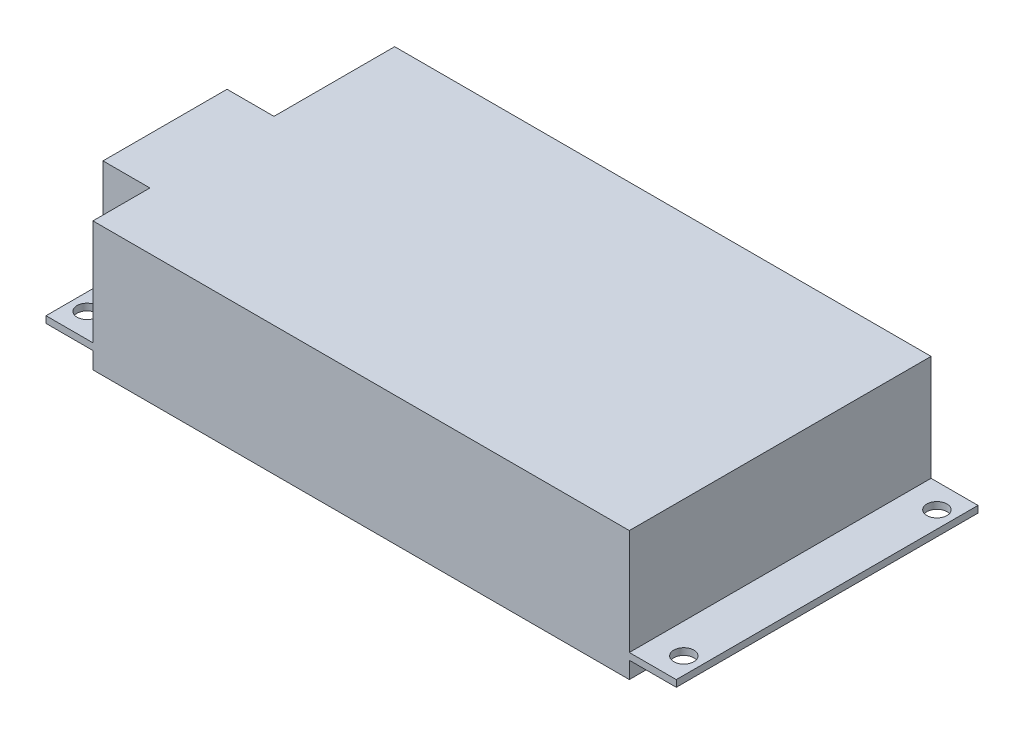
SolidWorks part; units mm, degrees
ref_plane "Front Plane" through (0, 0, 0) normal (0, 0, 1) x (1, 0, 0)
ref_plane "Top Plane" through (0, 0, 0) normal (0, 1, 0) x (1, 0, 0)
ref_plane "Right Plane" through (0, 0, 0) normal (1, 0, 0) x (0, 0, -1)
sketch "Sketch1" plane through (0, 0, 0) normal (0, 1, 0) x (1, 0, 0)
  line L1 (-94, -45) -> (94, -45)
  line L2 (-94, -45) -> (-94, 45)
  line L3 (-94, 45) -> (94, 45)
  line L4 (94, -45) -> (94, 45)
  line L5 (-94, -45) -> (94, 45) construction
  line L6 (-94, 45) -> (94, -45) construction
  line L7 (-89, -37.75) -> (89, -37.75) construction
  line L8 (-89, -37.75) -> (-89, 37.75) construction
  line L9 (-89, 37.75) -> (89, 37.75) construction
  line L10 (89, -37.75) -> (89, 37.75) construction
  line L11 (-89, -37.75) -> (89, 37.75) construction
  line L12 (-89, 37.75) -> (89, -37.75) construction
  circle A0 centre (-89, 37.75) radius 3
  circle A1 centre (89, 37.75) radius 3
  circle A2 centre (89, -37.75) radius 3
  circle A3 centre (-89, -37.75) radius 3
  point P0 (0, 0)
  point P6 (0, 0)
  dimension "D5" = 6
  dimension "D1" = 188
  dimension "D2" = 90
  dimension "D3" = 178
  dimension "D4" = 75.5
extrude "Boss-Extrude1" add sketch "Sketch1" along normal blind 2
sketch "Sketch2" plane through (0, 2, 0) normal (0, 1, 0) x (1, 0, 0)
  line L0 (94, 45) -> (-94, 45) construction
  line L1 (-80, -45) -> (80, -45)
  line L2 (-80, -45) -> (-80, 45)
  line L3 (-80, 45) -> (80, 45)
  line L4 (80, -45) -> (80, 45)
  line L5 (-80, -45) -> (80, 45) construction
  line L6 (-80, 45) -> (80, -45) construction
  line L7 (-94, 45) -> (-94, -45) construction
  line L8 (-80, 9) -> (-94, 9)
  line L9 (-80, 9) -> (-80, -28)
  line L10 (-80, -28) -> (-94, -28)
  line L11 (-94, 9) -> (-94, -28)
  point P0 (0, 0)
  line M10 (94, 45) -> (-94, 45)
  line M11 (-94, 45) -> (-94, -45)
  line M12 (-94, -45) -> (94, -45)
  dimension "D1" = 160
  dimension "D2" = 36
  dimension "D3" = 37
extrude "Boss-Extrude2" add sketch "Sketch2" along normal blind 31.5 and the other way blind 7 contours L4 L2 M12 M10 | L10 L2 L8 M11
